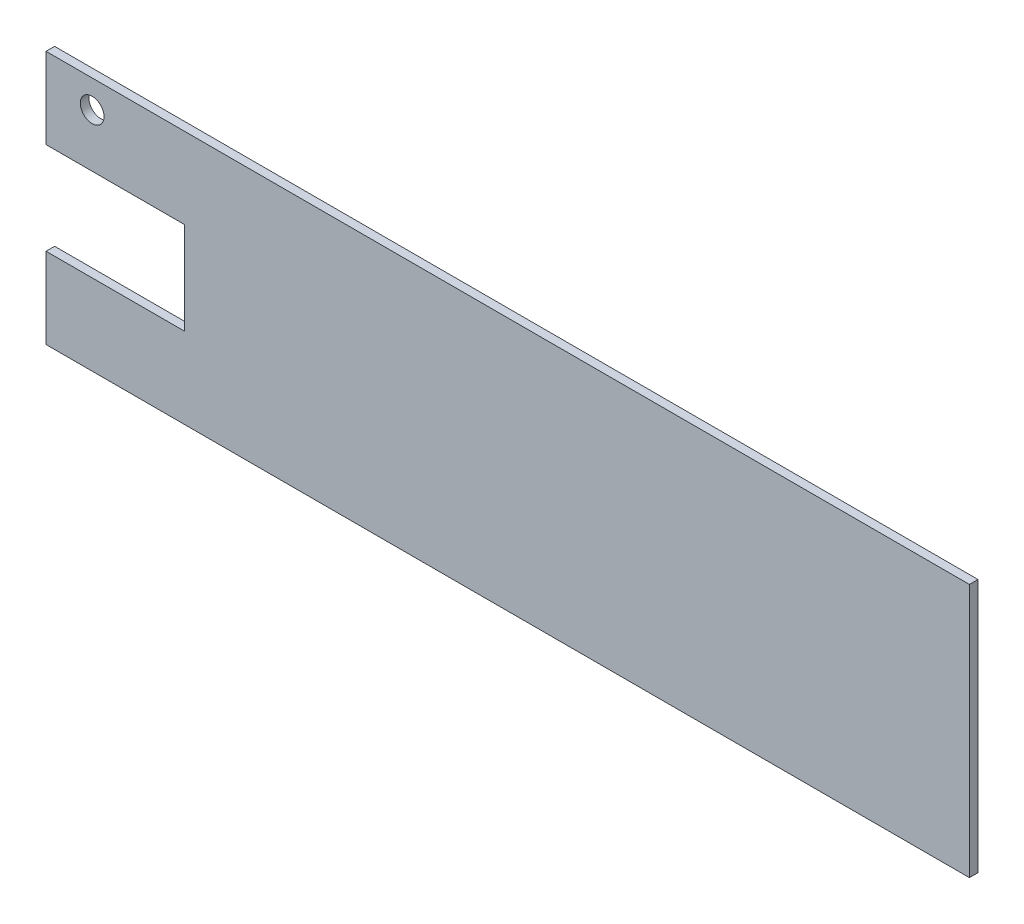
SolidWorks part; units mm, degrees
ref_plane "Front Plane" through (0, 0, 0) normal (0, 0, 1) x (1, 0, 0)
ref_plane "Top Plane" through (0, 0, 0) normal (0, 1, 0) x (1, 0, 0)
ref_plane "Right Plane" through (0, 0, 0) normal (1, 0, 0) x (0, 0, -1)
sketch "Sketch1" plane through (0, 0, 0) normal (0, 0, 1) x (1, 0, 0)
  line L1 (0, 0) -> (254, 0)
  line L2 (0, 0) -> (0, 69.85)
  line L3 (0, 69.85) -> (254, 69.85)
  line L4 (254, 0) -> (254, 69.85)
  dimension "D1" = 69.85
  dimension "D2" = 254
extrude "Boss-Extrude1" add sketch "Sketch1" along normal blind 2.3622
sketch "Sketch2" plane through (0, 0, 2.3622) normal (0, 0, 1) x (1, 0, 0)
  line L0 (0, 69.85) -> (0, 0) construction
  line L1 (0, 47.625) -> (38.1, 47.625)
  line L2 (0, 47.625) -> (0, 22.225)
  line L3 (0, 22.225) -> (38.1, 22.225)
  line L4 (38.1, 47.625) -> (38.1, 22.225)
  line L5 (254, 0) -> (254, 69.85) construction
  point P6 (38.1, 34.925)
  point P7 (254, 34.925)
  dimension "D1" = 25.4
  dimension "D2" = 38.1
extrude "Cut-Extrude1" cut sketch "Sketch2" against normal through all
sketch "Sketch3" plane through (0, 0, 2.3622) normal (0, 0, 1) x (1, 0, 0)
  line L0 (0, 69.85) -> (0, 47.625) construction
  line L1 (254, 69.85) -> (0, 69.85) construction
  circle A0 centre (12.7, 62.23) radius 3.2639
  dimension "D1" = 6.5278
  dimension "D2" = 12.7
  dimension "D3" = 7.62
extrude "Cut-Extrude2" cut sketch "Sketch3" against normal through all
